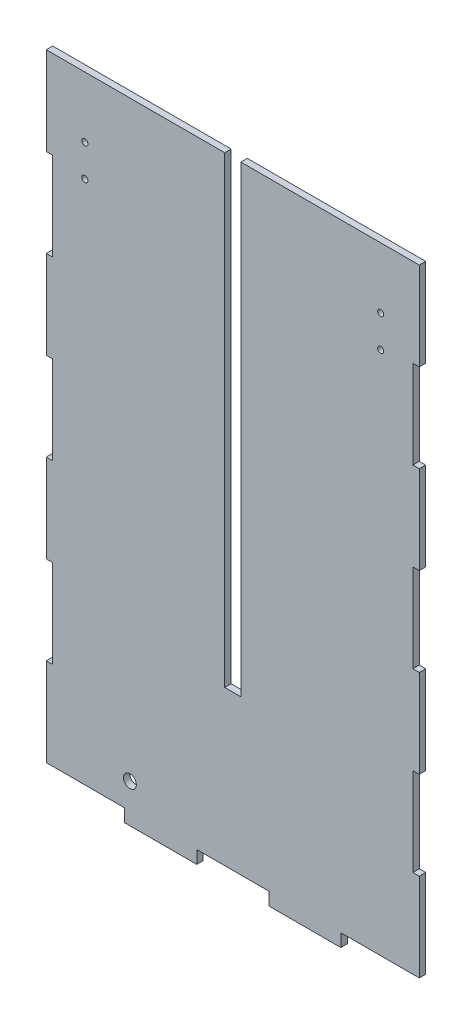
SolidWorks part; units mm, degrees
ref_plane "Front Plane" through (0, 0, 0) normal (0, 0, 1) x (1, 0, 0)
ref_plane "Top Plane" through (0, 0, 0) normal (0, 1, 0) x (1, 0, 0)
ref_plane "Right Plane" through (0, 0, 0) normal (1, 0, 0) x (0, 0, -1)
sketch "Sketch2" plane through (0, 0, 0) normal (0, 0, 1) x (1, 0, 0)
  line L0 (0, 152.4) -> (0, -152.4) construction
  line L1 (-88.9, 152.4) -> (88.9, 152.4)
  line L2 (-88.9, 152.4) -> (-88.9, -152.4)
  line L3 (-88.9, -152.4) -> (88.9, -152.4)
  line L4 (88.9, 152.4) -> (88.9, -152.4)
  line L5 (-88.9, 108.8571) -> (-88.9, 65.3143)
  line L6 (-88.9, 152.4) -> (-92.075, 152.4)
  line L7 (-88.9, 152.4) -> (-88.9, 108.8571)
  line L8 (-88.9, 108.8571) -> (-92.075, 108.8571)
  line L9 (-92.075, 152.4) -> (-92.075, 108.8571)
  line L10 (88.9, 152.4) -> (92.075, 152.4)
  line L11 (88.9, 152.4) -> (88.9, 108.8571)
  line L12 (88.9, 108.8571) -> (92.075, 108.8571)
  line L13 (92.075, 152.4) -> (92.075, 108.8571)
  line L18 (-88.9, 108.8571) -> (-92.075, 108.8571)
  line L19 (-92.075, 108.8571) -> (-92.075, 65.3143)
  line L20 (-88.9, 65.3143) -> (-92.075, 65.3143)
  line L21 (88.9, 108.8571) -> (88.9, 65.3143)
  line L22 (88.9, 108.8571) -> (92.075, 108.8571)
  line L23 (92.075, 108.8571) -> (92.075, 65.3143)
  line L24 (88.9, 65.3143) -> (92.075, 65.3143)
  line L25 (-88.9, 65.3143) -> (-88.9, 21.7714)
  line L26 (-88.9, 65.3143) -> (-92.075, 65.3143)
  line L27 (-92.075, 65.3143) -> (-92.075, 21.7714)
  line L28 (-88.9, 21.7714) -> (-92.075, 21.7714)
  line L29 (88.9, 65.3143) -> (88.9, 21.7714)
  line L30 (88.9, 65.3143) -> (92.075, 65.3143)
  line L31 (92.075, 65.3143) -> (92.075, 21.7714)
  line L32 (88.9, 21.7714) -> (92.075, 21.7714)
  line L33 (-88.9, 21.7714) -> (-88.9, -21.7714)
  line L34 (-88.9, 21.7714) -> (-92.075, 21.7714)
  line L35 (-92.075, 21.7714) -> (-92.075, -21.7714)
  line L36 (-88.9, -21.7714) -> (-92.075, -21.7714)
  line L37 (88.9, 21.7714) -> (88.9, -21.7714)
  line L38 (88.9, 21.7714) -> (92.075, 21.7714)
  line L39 (92.075, 21.7714) -> (92.075, -21.7714)
  line L40 (88.9, -21.7714) -> (92.075, -21.7714)
  line L41 (-88.9, -21.7714) -> (-88.9, -65.3143)
  line L42 (-88.9, -21.7714) -> (-92.075, -21.7714)
  line L43 (-92.075, -21.7714) -> (-92.075, -65.3143)
  line L44 (-88.9, -65.3143) -> (-92.075, -65.3143)
  line L45 (88.9, -21.7714) -> (88.9, -65.3143)
  line L46 (88.9, -21.7714) -> (92.075, -21.7714)
  line L47 (92.075, -21.7714) -> (92.075, -65.3143)
  line L48 (88.9, -65.3143) -> (92.075, -65.3143)
  line L49 (-88.9, -65.3143) -> (-88.9, -108.8571)
  line L50 (-88.9, -65.3143) -> (-92.075, -65.3143)
  line L51 (-92.075, -65.3143) -> (-92.075, -108.8571)
  line L52 (-88.9, -108.8571) -> (-92.075, -108.8571)
  line L53 (88.9, -65.3143) -> (88.9, -108.8571)
  line L54 (88.9, -65.3143) -> (92.075, -65.3143)
  line L55 (92.075, -65.3143) -> (92.075, -108.8571)
  line L56 (88.9, -108.8571) -> (92.075, -108.8571)
  line L57 (-88.9, -108.8571) -> (-88.9, -152.4)
  line L58 (-88.9, -108.8571) -> (-92.075, -108.8571)
  line L59 (-92.075, -108.8571) -> (-92.075, -152.4)
  line L60 (-88.9, -152.4) -> (-92.075, -152.4)
  line L61 (88.9, -108.8571) -> (88.9, -152.4)
  line L62 (88.9, -108.8571) -> (92.075, -108.8571)
  line L63 (92.075, -108.8571) -> (92.075, -152.4)
  line L64 (88.9, -152.4) -> (92.075, -152.4)
  line L89 (-88.9, -152.4) -> (-88.9, -158.75)
  line L90 (-88.9, -158.75) -> (-53.34, -158.75)
  line L91 (-53.34, -158.75) -> (-53.34, -152.4)
  line L92 (-53.34, -152.4) -> (-88.9, -152.4)
  line L93 (-53.34, -152.4) -> (-53.34, -158.75)
  line L94 (-53.34, -158.75) -> (-17.78, -158.75)
  line L95 (-17.78, -158.75) -> (-17.78, -152.4)
  line L96 (-17.78, -152.4) -> (-53.34, -152.4)
  line L97 (-17.78, -152.4) -> (-17.78, -158.75)
  line L98 (-17.78, -158.75) -> (17.78, -158.75)
  line L99 (17.78, -158.75) -> (17.78, -152.4)
  line L100 (17.78, -152.4) -> (-17.78, -152.4)
  line L101 (17.78, -152.4) -> (17.78, -158.75)
  line L102 (17.78, -158.75) -> (53.34, -158.75)
  line L103 (53.34, -158.75) -> (53.34, -152.4)
  line L104 (53.34, -152.4) -> (17.78, -152.4)
  line L105 (53.34, -152.4) -> (53.34, -158.75)
  line L106 (53.34, -158.75) -> (88.9, -158.75)
  line L107 (88.9, -158.75) -> (88.9, -152.4)
  line L108 (88.9, -152.4) -> (53.34, -152.4)
  line L109 (-88.9, -152.4) -> (-53.34, -152.4) construction
  point P6 (0, 0)
  dimension "D1" = 177.8
  dimension "D2" = 184.15
  dimension "D3" = 304.8
  dimension "D6" = 43.5429
  dimension "D4" = 6.35
  dimension "D8" = 35.56
  dimension "D9" = 35.56
  dimension "D5" = 7
  dimension "D7" = 5
extrude "Boss-Extrude1" add sketch "Sketch2" along normal blind 3.175 contours L4 L1 L2 L3 | L94 L95 L3 L91 | L102 L103 L3 L99 | L60 L2 L52 L59 | L44 L2 L36 L43 | L28 L2 L20 L27 | L6 L9 L8 L2 | L13 L10 L4 L12 | L4 L32 L31 L24 | L4 L48 L47 L40 | L4 L64 L63 L56 | L105 L106 L107 L108
sketch "Sketch3" plane through (0, 0, 3.175) normal (0, 0, 1) x (1, 0, 0)
  line L0 (-92.075, 152.4) -> (92.075, 152.4) construction
  line L1 (-3.9688, 152.4) -> (3.9687, 152.4)
  line L2 (-3.9688, 152.4) -> (-3.9687, -76.2)
  line L3 (-3.9687, -76.2) -> (3.9688, -76.2)
  line L4 (3.9687, 152.4) -> (3.9688, -76.2)
  line L5 (0, -76.2) -> (0, 0) construction
  dimension "D1" = 7.9375
  dimension "D2" = 228.6
extrude "Cut-Extrude1" cut sketch "Sketch3" against normal through all
sketch "Sketch4" plane through (0, 0, 3.175) normal (0, 0, 1) x (1, 0, 0)
  line L2 (-88.9, -65.3143) -> (-88.9, -108.8571) construction
  line L3 (-92.075, -152.4) -> (-53.34, -152.4) construction
  circle A0 centre (-50.8, -139.7) radius 3.175
  dimension "D1" = 6.35
  dimension "D2" = 12.7
  dimension "D3" = 38.1
extrude "Cut-Extrude2" cut sketch "Sketch4" against normal through all
sketch "Sketch5" plane through (0, 0, 3.175) normal (0, 0, 1) x (1, 0, 0)
  line L1 (-92.075, 152.4) -> (-3.9688, 152.4) construction
  line L2 (0, -152.4) -> (0, 152.4) construction
  line L3 (-17.78, -152.4) -> (17.78, -152.4) construction
  line L4 (-92.075, 152.4) -> (-92.075, 108.8571) construction
  circle A0 centre (-73.025, 122.4) radius 1.5
  circle A1 centre (-73.025, 106.65) radius 1.5
  circle A2 centre (73.025, 122.4) radius 1.5
  circle A3 centre (73.025, 106.65) radius 1.5
  dimension "D1" = 3
  dimension "D2" = 3
  dimension "D3" = 15.75
  dimension "D4" = 19.05
  dimension "D5" = 30
extrude "Cut-Extrude3" cut sketch "Sketch5" against normal up to surface (3.175 mm away) up to face at (-47.625, -139.7, 0)
equation "\"Height\"= 12in"
equation "\"Depth\"= 7in"
equation "\"WallThickness\"= 0.125in"
equation "\"FloorThickness\"= 0.25in"
equation "\"D1@Sketch2\"=\"Depth\""
equation "\"D2@Sketch2\"=\"D1@Sketch2\"+2*\"WallThickness\""
equation "\"D3@Sketch2\"=\"Height\""
equation "\"D6@Sketch2\"=\"D3@Sketch2\"/\"D5@Sketch2\""
equation "\"D1@Boss-Extrude1\"=\"WallThickness\""
equation "\"Width\" = 30in"
equation "\"D4@Sketch2\"=\"FloorThickness\""
equation "\"D9@Sketch2\"=\"D1@Sketch2\"/\"D7@Sketch2\""
equation "\"D8@Sketch2\"=\"D9@Sketch2\""
